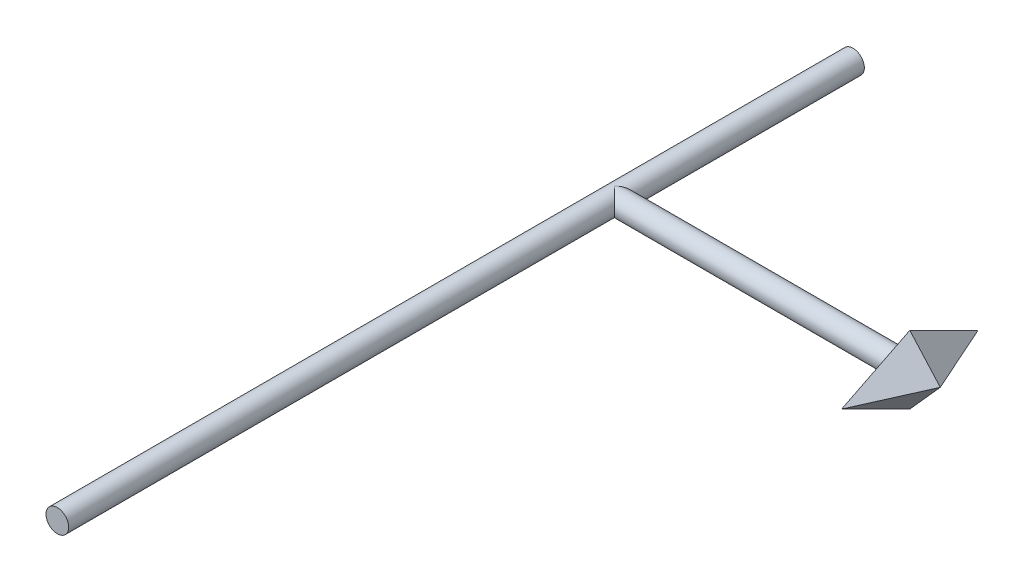
SolidWorks part; units mm, degrees
ref_plane "Front Plane" through (0, 0, 0) normal (0, 0, 1) x (1, 0, 0)
ref_plane "Top Plane" through (0, 0, 0) normal (0, 1, 0) x (1, 0, 0)
ref_plane "Right Plane" through (0, 0, 0) normal (1, 0, 0) x (0, 0, -1)
sketch "Sketch1" plane through (0, 0, 0) normal (0, 0, 1) x (1, 0, 0)
  circle A0 centre (0, 0) radius 5
  dimension "D1" = 10
extrude "Boss-Extrude1" add sketch "Sketch1" along normal blind 600
sketch "Sketch2" plane through (0, 0, 0) normal (0, 1, 0) x (1, 0, 0)
  circle A0 centre (0, -145) radius 5
  dimension "D1" = 10
  dimension "D2" = 145
extrude "Boss-Extrude2" add sketch "Sketch2" along normal blind 130
sketch "Sketch4" plane through (0, 130, 0) normal (0, 1, 0) x (1, 0, 0)
  line L1 (0, -115) -> (0, -175) construction
  line L3 (-15, -145) -> (15, -145) construction
  line L4 (0, -115) -> (-15, -145)
  line L5 (-15, -145) -> (0, -175)
  line L6 (0, -115) -> (15, -145)
  line L7 (15, -145) -> (0, -175)
  point P1 (0, -145)
  dimension "D1" = 60
  dimension "D2" = 30
extrude "Boss-Extrude3" add sketch "Sketch4" along normal blind 130 draft 45
sketch "Sketch5" plane through (0, 0, 0) normal (1, 0, 0) x (0, 0, -1)
  circle A0 centre (-355, 0) radius 5
  dimension "D1" = 10
  dimension "D2" = 355
extrude "Boss-Extrude4" add sketch "Sketch5" along normal blind 130
sketch "Sketch6" plane through (130, 0, 0) normal (1, 0, 0) x (0, 0, -1)
  line L0 (-355, 15) -> (-355, -15) construction
  line L1 (-385, 0) -> (-325, 0) construction
  line L2 (-355, 15) -> (-385, 0)
  line L3 (-385, 0) -> (-355, -15)
  line L4 (-355, 15) -> (-325, 0)
  line L5 (-325, 0) -> (-355, -15)
  point P1 (-355, 0)
  dimension "D1" = 30
  dimension "D2" = 60
extrude "Boss-Extrude5" add sketch "Sketch6" along normal blind 130 draft 45
sketch "Sketch7" plane through (0, 0, 0) normal (0, 1, 0) x (1, 0, 0)
  line L0 (5, 0) -> (-5, 0) construction
  line L1 (-354.6145, 250) -> (354.6145, 250)
  line L2 (-354.6145, 250) -> (-354.6145, -250)
  line L3 (-354.6145, -250) -> (354.6145, -250)
  line L4 (354.6145, 250) -> (354.6145, -250)
  line L5 (-354.6145, 250) -> (354.6145, -250) construction
  line L6 (-354.6145, -250) -> (354.6145, 250) construction
  point P0 (0, 0)
  point P5 (0, 0)
  point P6 (268.6165, -638.0138)
  point P7 (354.6145, -250.7949)
  dimension "D1" = 250
  dimension "D2" = 500
extrude "Cut-Extrude1" cut sketch "Sketch7" against normal mid plane 500
